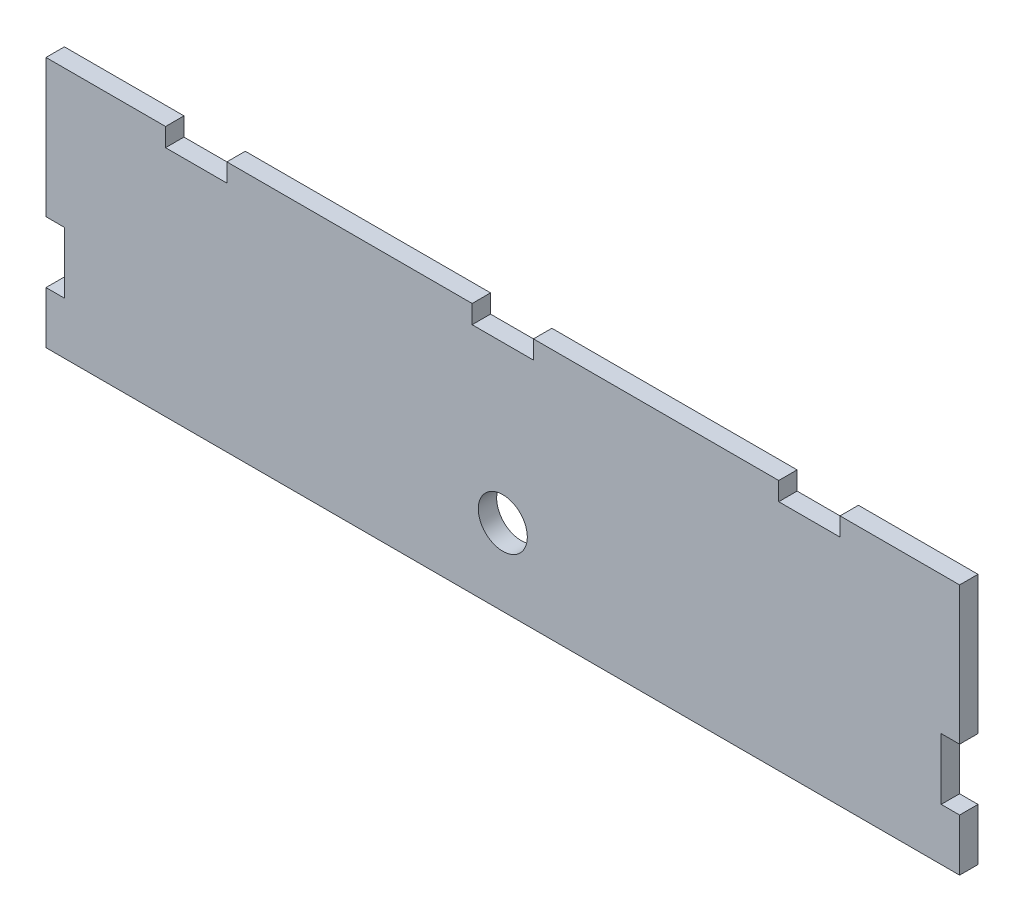
SolidWorks part; units mm, degrees
ref_plane "Front Plane" through (0, 0, 0) normal (0, 0, 1) x (1, 0, 0)
ref_plane "Top Plane" through (0, 0, 0) normal (0, 1, 0) x (1, 0, 0)
ref_plane "Right Plane" through (0, 0, 0) normal (1, 0, 0) x (0, 0, -1)
sketch "Sketch1" plane through (0, 0, 0) normal (0, 0, 1) x (1, 0, 0)
  line L2 (-74.5, 14) -> (-74.5, -8.5)
  line L3 (-74.5, -27) -> (74.5, -27)
  line L4 (74.5, 14) -> (74.5, -8.5)
  line L7 (-5, 14) -> (-5, 11)
  line L8 (-5, 11) -> (5, 11)
  line L9 (5, 14) -> (5, 11)
  line L11 (45, 14) -> (45, 11)
  line L12 (45, 11) -> (55, 11)
  line L13 (55, 14) -> (55, 11)
  line L27 (71.5, -8.5) -> (74.5, -8.5)
  line L28 (71.5, -8.5) -> (71.5, -18.5)
  line L29 (71.5, -18.5) -> (74.5, -18.5)
  line L31 (-71.5, -18.5) -> (-74.5, -18.5)
  line L32 (-71.5, -8.5) -> (-71.5, -18.5)
  line L33 (-71.5, -8.5) -> (-74.5, -8.5)
  line L34 (-74.5, -18.5) -> (-74.5, -27)
  line L35 (74.5, -18.5) -> (74.5, -27)
  line L37 (-55, 14) -> (-55, 11)
  line L38 (-45, 11) -> (-55, 11)
  line L39 (-45, 14) -> (-45, 11)
  line L41 (74.5, 14) -> (55, 14)
  line L42 (-55, 14) -> (-74.5, 14)
  line L43 (-5, 14) -> (-45, 14)
  line L44 (45, 14) -> (5, 14)
  dimension "D1" = 3
  dimension "D2" = 149
  dimension "D3" = 3
  dimension "D4" = 41
  dimension "D5" = 10
  dimension "D7" = 3
  dimension "D8" = 10
  dimension "D9" = 8.5
  dimension "D6" = 40
extrude "Boss-Extrude1" add sketch "Sketch1" along normal blind 3
sketch "Sketch2" plane through (0, 0, 0) normal (0, 0, 1) x (1, 0, 0)
  line L0 (-74.5, -27) -> (74.5, -27) construction
  line L1 (0, -1.65) -> (0, 1.65) construction
  circle A0 centre (0, -14.5) radius 4
  dimension "D1" = 8
  dimension "D2" = 12.5
extrude "Cut-Extrude1" cut sketch "Sketch2" along normal through all
